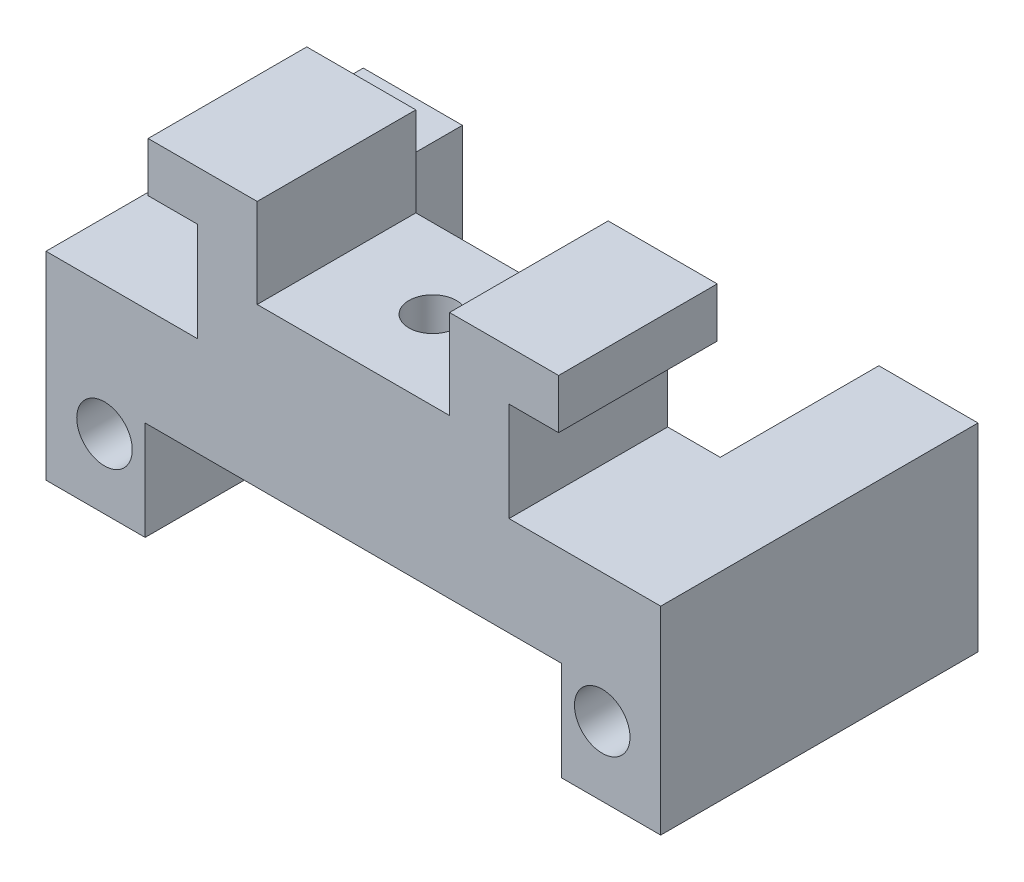
SolidWorks part; units mm, degrees
ref_plane "Plan de face" through (0, 0, 0) normal (0, 0, 1) x (1, 0, 0)
ref_plane "Plan de dessus" through (0, 0, 0) normal (0, 1, 0) x (1, 0, 0)
ref_plane "Plan de droite" through (0, 0, 0) normal (1, 0, 0) x (0, 0, -1)
sketch "Esquisse1" plane through (0, 0, 0) normal (0, 0, 1) x (1, 0, 0)
  line L0 (-32.764, 3.5) -> (28.0862, 3.5) construction
  line L1 (-10.5, -5) -> (10.5, -5) construction
  line L2 (-10.5, -5) -> (-10.5, 5) construction
  line L3 (-10.5, 5) -> (10.5, 5) construction
  line L4 (10.5, -5) -> (10.5, 5) construction
  line L5 (-10.5, -5) -> (10.5, 5) construction
  line L6 (-10.5, 5) -> (10.5, -5) construction
  line L7 (0, 0) -> (0, 18.1795) construction
  line L8 (15.5, 10) -> (-15.5, 10)
  line L9 (10.5, 0) -> (15.5, 0)
  line L10 (10.5, 0) -> (10.5, 5)
  line L11 (10.5, 5) -> (-10.5, 5)
  line L12 (15.5, 0) -> (15.5, 10)
  line L13 (-10.5, 0) -> (-15.5, 0)
  line L14 (-15.5, 0) -> (-15.5, 10)
  line L15 (-10.5, 0) -> (-10.5, 5)
  circle A0 centre (12.55, 3.5) radius 1.4
  circle A1 centre (-12.55, 3.5) radius 1.4
  point P0 (0, 0)
  point P19 (0, 10)
  point P22 (0, 5)
  dimension "D3" = 12.55
  dimension "D5" = 5
  dimension "D1" = 21
  dimension "D2" = 10
  dimension "D4" = 1.5
  dimension "D6" = 10
extrude "Boss.-Extru.1" add sketch "Esquisse1" along normal blind 16
sketch "Esquisse2" plane through (0, 10, 0) normal (0, 1, 0) x (1, 0, 0)
  line L0 (0, -16) -> (0, 0) construction
  line L1 (-15.5, 0) -> (15.5, 0) construction
  line L2 (-15.5, 0) -> (-15.5, -16) construction
  line L3 (-15.5, -16) -> (15.5, -16) construction
  line L4 (15.5, 0) -> (15.5, -16) construction
  line L5 (7.85, -16) -> (7.85, 0)
  line L6 (7.85, -16) -> (-7.85, -16)
  line L8 (7.85, 0) -> (-7.85, 0)
  line L9 (-7.85, -16) -> (-7.85, 0)
  dimension "D1" = 7.85
extrude "Boss.-Extru.2" add sketch "Esquisse2" along normal blind 15
sketch "Esquisse3" plane through (0, 0, 16) normal (0, 0, 1) x (1, 0, 0)
  line L0 (-7.85, 10) -> (7.85, 10) construction
  line L1 (0, 10) -> (0, 25) construction
  line L2 (-7.85, 25) -> (7.85, 25) construction
  circle A0 centre (0, 17.5) radius 4
  dimension "D1" = 7.5
extrude "Enlèv. mat.-Extru.1" cut sketch "Esquisse3" against normal blind 15 contours A0
sketch "Esquisse4" plane through (0, 5, 0) normal (0, -1, 0) x (1, 0, 0)
  line L0 (10.5, 16) -> (10.5, 0) construction
  line L1 (-10.5, 0) -> (10.5, 0)
  line L2 (-10.5, 0) -> (-10.5, 8)
  line L3 (-10.5, 8) -> (10.5, 8)
  line L4 (10.5, 0) -> (10.5, 8)
extrude "Enlèv. mat.-Extru.2" cut sketch "Esquisse4" against normal blind 21
sketch "Esquisse5" plane through (-7.85, 0, 0) normal (-1, 0, 0) x (0, 0, 1)
  line L0 (12, 25) -> (12, 10) construction
  line L1 (8, 25) -> (16, 25) construction
  line L2 (8, 10) -> (16, 10) construction
  circle A0 centre (12, 17.5) radius 1.4
  dimension "D1" = 7.5
extrude "Enlèv. mat.-Extru.3" cut sketch "Esquisse5" against normal blind 21
sketch "Esquisse6" plane through (0, 0, 16) normal (0, 0, 1) x (1, 0, 0)
  line L1 (-10.364, 13) -> (7.85, 13)
  line L2 (-10.364, 13) -> (-10.364, 25)
  line L3 (-10.364, 25) -> (7.85, 25)
  line L4 (7.85, 13) -> (7.85, 25)
  dimension "D1" = 12
extrude "Enlèv. mat.-Extru.4" cut sketch "Esquisse6" against normal blind 10
sketch "Esquisse7" plane through (0, 5, 0) normal (0, -1, 0) x (1, 0, 0)
  line L0 (0, 16) -> (0, 8) construction
  line L1 (-10.5, 16) -> (10.5, 16) construction
  line L2 (10.5, 8) -> (-10.5, 8) construction
  circle A0 centre (0, 12) radius 1.2
extrude "Enlèv. mat.-Extru.5" cut sketch "Esquisse7" against normal through all
sketch "Esquisse8" plane through (0, 0, 16) normal (0, 0, 1) x (1, 0, 0)
  line L0 (-7.85, 13) -> (-7.85, 15)
  line L1 (-7.85, 15) -> (-10.35, 15)
  line L2 (-10.35, 15) -> (-10.35, 17.5)
  line L3 (-10.35, 17.5) -> (-4.85, 17.5)
  line L4 (-4.85, 17.5) -> (-4.85, 13)
  line L5 (-7.85, 13) -> (7.85, 13) construction
  line L6 (-4.85, 13) -> (-7.85, 13)
  line L7 (0, 13) -> (0, 5) construction
  line L8 (-10.5, 5) -> (10.5, 5) construction
  line L9 (4.85, 13) -> (7.85, 13)
  line L10 (7.85, 13) -> (7.85, 15)
  line L11 (7.85, 15) -> (10.35, 15)
  line L12 (10.35, 15) -> (10.35, 17.5)
  line L13 (10.35, 17.5) -> (4.85, 17.5)
  line L14 (4.85, 17.5) -> (4.85, 13)
  dimension "D1" = 3
  dimension "D2" = 2
  dimension "D3" = 2.5
  dimension "D4" = 2.5
extrude "Boss.-Extru.3" add sketch "Esquisse8" against normal blind 8
